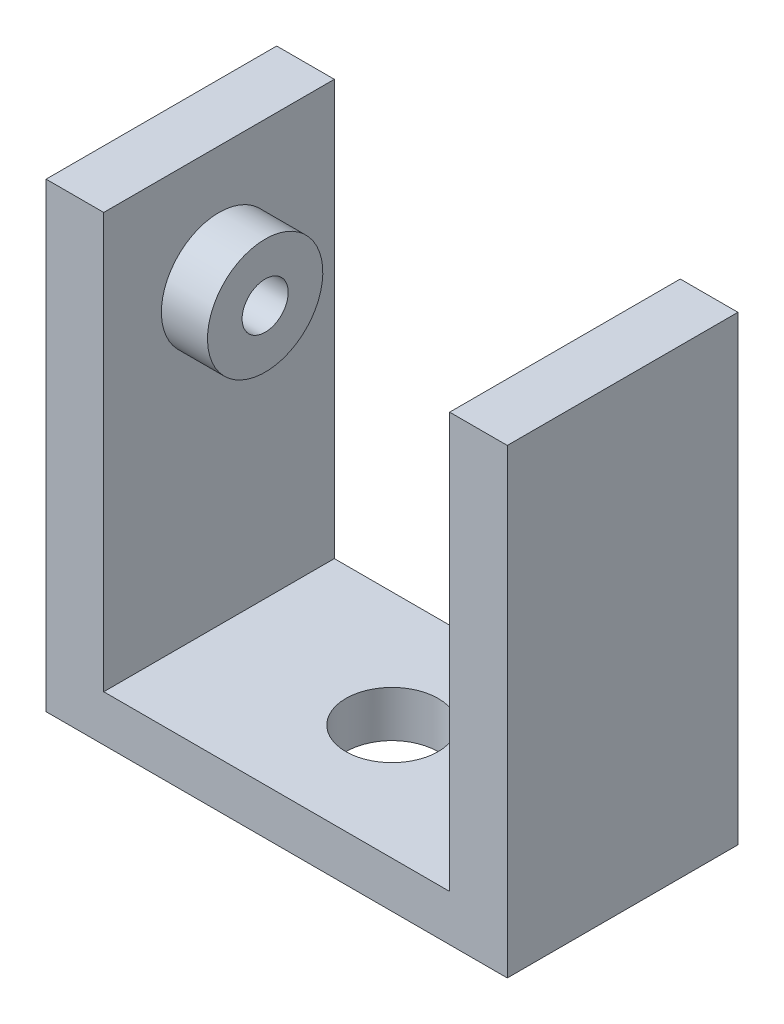
SolidWorks part; units mm, degrees
ref_plane "前视基准面" through (0, 0, 0) normal (0, 0, 1) x (1, 0, 0)
ref_plane "上视基准面" through (0, 0, 0) normal (0, 1, 0) x (1, 0, 0)
ref_plane "右视基准面" through (0, 0, 0) normal (1, 0, 0) x (0, 0, -1)
other "Configuration Table"
sketch "草图1" plane through (0, 0, 0) normal (0, 1, 0) x (1, 0, 0)
  line L1 (-20, 10) -> (20, 10)
  line L2 (-20, 10) -> (-20, -10)
  line L3 (-20, -10) -> (20, -10)
  line L4 (20, 10) -> (20, -10)
  line L5 (-20, 10) -> (20, -10) construction
  line L6 (-20, -10) -> (20, 10) construction
  point P0 (0, 0)
  dimension "D1" = 20
  dimension "D2" = 40
extrude "凸台-拉伸1" add sketch "草图1" along normal blind 40
sketch "草图2" plane through (0, 0, 10) normal (0, 0, 1) x (1, 0, 0)
  line L0 (-15, 40) -> (-15, 4)
  line L1 (-20, 40) -> (20, 40) construction
  line L2 (-15, 4) -> (15, 4)
  line L3 (15, 4) -> (15, 40)
  line L4 (-20, 40) -> (-20, 0) construction
  line L5 (20, 40) -> (20, 0) construction
  line L6 (-20, 0) -> (20, 0) construction
  dimension "D1" = 5
  dimension "D2" = 5
  dimension "D3" = 4
extrude "切除-拉伸1" cut sketch "草图2" against normal through all and the other way through all
sketch "草图3" plane through (-20, 0, 0) normal (-1, 0, 0) x (0, 0, 1)
  circle A0 centre (0, 30) radius 2
sketch "草图4" plane through (0, 0, 0) normal (0, -1, 0) x (1, 0, 0)
  circle A0 centre (0, 0) radius 4
extrude "切除-拉伸3" cut sketch "草图4" against normal through all
sketch "草图5" plane through (-15, 0, 0) normal (1, 0, 0) x (0, 0, -1)
  circle A0 centre (0, 30) radius 5
  circle A1 centre (0, 30) radius 2
extrude "凸台-拉伸2" add sketch "草图5" along normal blind 4
mirror "镜向1" about plane through (0, 0, 0) normal (1, 0, 0) of "凸台-拉伸2"
